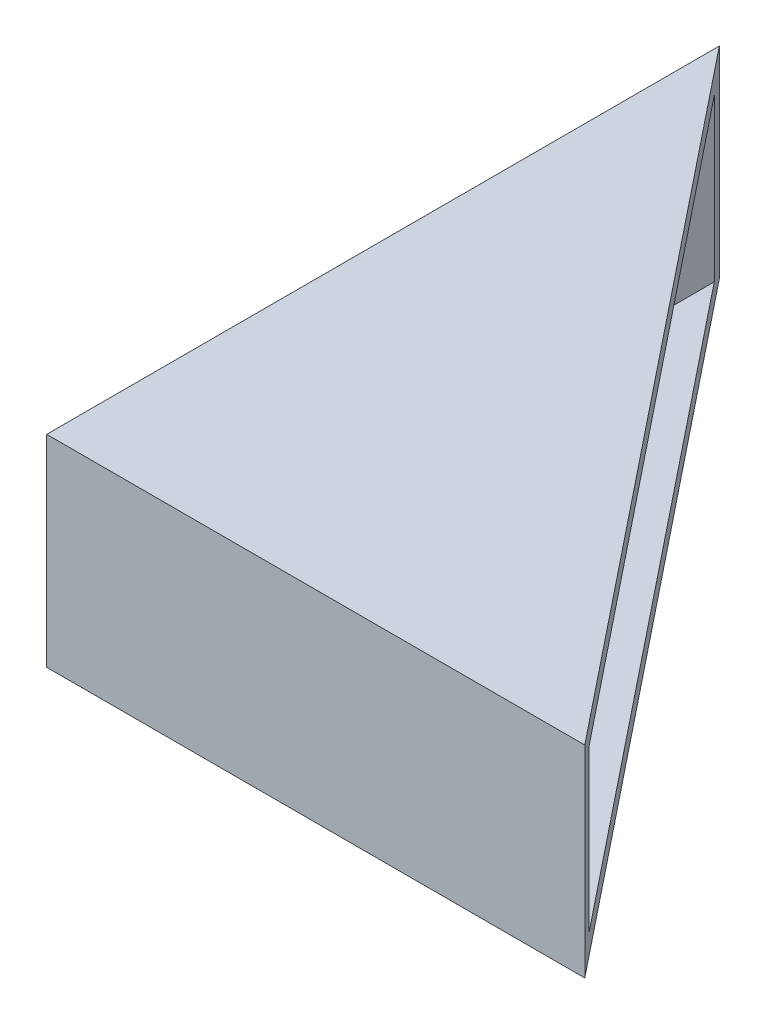
SolidWorks part; units mm, degrees
ref_plane "前视基准面" through (0, 0, 0) normal (0, 0, 1) x (1, 0, 0)
ref_plane "上视基准面" through (0, 0, 0) normal (0, 1, 0) x (1, 0, 0)
ref_plane "右视基准面" through (0, 0, 0) normal (1, 0, 0) x (0, 0, -1)
other "Configuration Table"
sketch "Sketch1" plane through (0, 0, 0) normal (0, 1, 0) x (1, 0, 0)
  line L0 (0, 0) -> (80, 0)
  line L1 (80, 0) -> (0, 100)
  line L2 (0, 100) -> (0, 0)
  dimension "D1" = 100
  dimension "D2" = 80
extrude "Boss-Extrude1" add sketch "Sketch1" along normal blind 30
shell "Shell1" thickness 3
sketch "Sketch2" plane through (0, 0, 0) normal (-1, 0, 0) x (0, 0, 1)
  line L0 (0, 15) -> (-100, 15) construction
  line L1 (0, 30) -> (0, 0) construction
  circle A0 centre (-15, 15) radius 1.75
  circle A1 centre (-40, 15) radius 1.75
  circle A2 centre (-65, 15) radius 1.75
  circle A3 centre (-90, 15) radius 1.75
  dimension "D2" = 3.5
  dimension "D3" = 3.5
  dimension "D4" = 15
  dimension "D5" = 25
  dimension "D1" = 100
  dimension "D6" = 3
extrude "Cut-Extrude1" cut sketch "Sketch2" against normal blind 10
